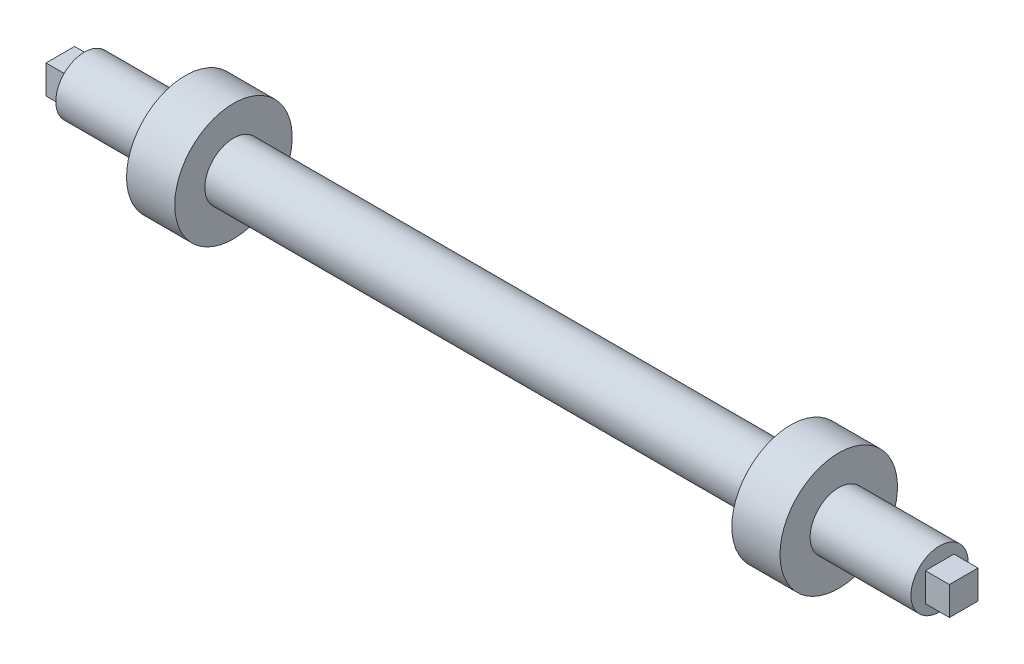
SolidWorks part; units mm, degrees
ref_plane "Plan de face" through (0, 0, 0) normal (0, 0, 1) x (1, 0, 0)
ref_plane "Plan de dessus" through (0, 0, 0) normal (0, 1, 0) x (1, 0, 0)
ref_plane "Plan de droite" through (0, 0, 0) normal (1, 0, 0) x (0, 0, -1)
sketch "Esquisse1" plane through (0, 0, 0) normal (0, 1, 0) x (1, 0, 0)
  line L0 (0, 0) -> (0, 4.75)
  line L1 (0, 4.75) -> (142, 4.75)
  line L2 (142, 4.75) -> (142, 0)
  line L24 (16.75, 0) -> (16.75, -5)
  line L25 (16.75, -5) -> (24.75, -5)
  line L26 (24.75, -5) -> (24.75, 0)
  line L27 (117.25, 0) -> (117.25, -5)
  line L28 (117.25, -5) -> (125.25, -5)
  line L29 (125.25, -5) -> (125.25, 0)
  line L30 (0, 0) -> (16.75, 0)
  line L31 (24.75, 0) -> (117.25, 0)
  line L32 (125.25, 0) -> (142, 0)
  dimension "D1" = 142
  dimension "D2" = 16.75
  dimension "D3" = 8
  dimension "D4" = 8
  dimension "D5" = 16.75
  dimension "D6" = 5
  dimension "D7" = 5
  dimension "D8" = 4.75
  dimension "D9" = 5
  dimension "D10" = 5
revolve "Révolution1" add sketch "Esquisse1" angle 360 about L1
sketch "Esquisse5" plane through (142, 0, 0) normal (1, 0, 0) x (0, 0, -1)
  line L0 (2.375, 2.375) -> (2.375, -2.375)
  line L9 (2.375, 2.375) -> (7.125, 2.375)
  line L10 (7.125, 2.375) -> (7.125, -2.375)
  line L11 (7.125, -2.375) -> (2.375, -2.375)
extrude "Boss.-Extru.3" add sketch "Esquisse5" along normal blind 4
sketch "Esquisse6" plane through (0, 0, 0) normal (-1, 0, 0) x (0, 0, 1)
  line L8 (-4.75, 2.375) -> (-7.125, 2.375)
  line L9 (-7.125, 2.375) -> (-7.125, -2.375)
  line L10 (-7.125, -2.375) -> (-2.375, -2.375)
  line L11 (-2.375, -2.375) -> (-2.375, 2.375)
  line L12 (-2.375, 2.375) -> (-4.75, 2.375)
extrude "Boss.-Extru.4" add sketch "Esquisse6" along normal blind 4
